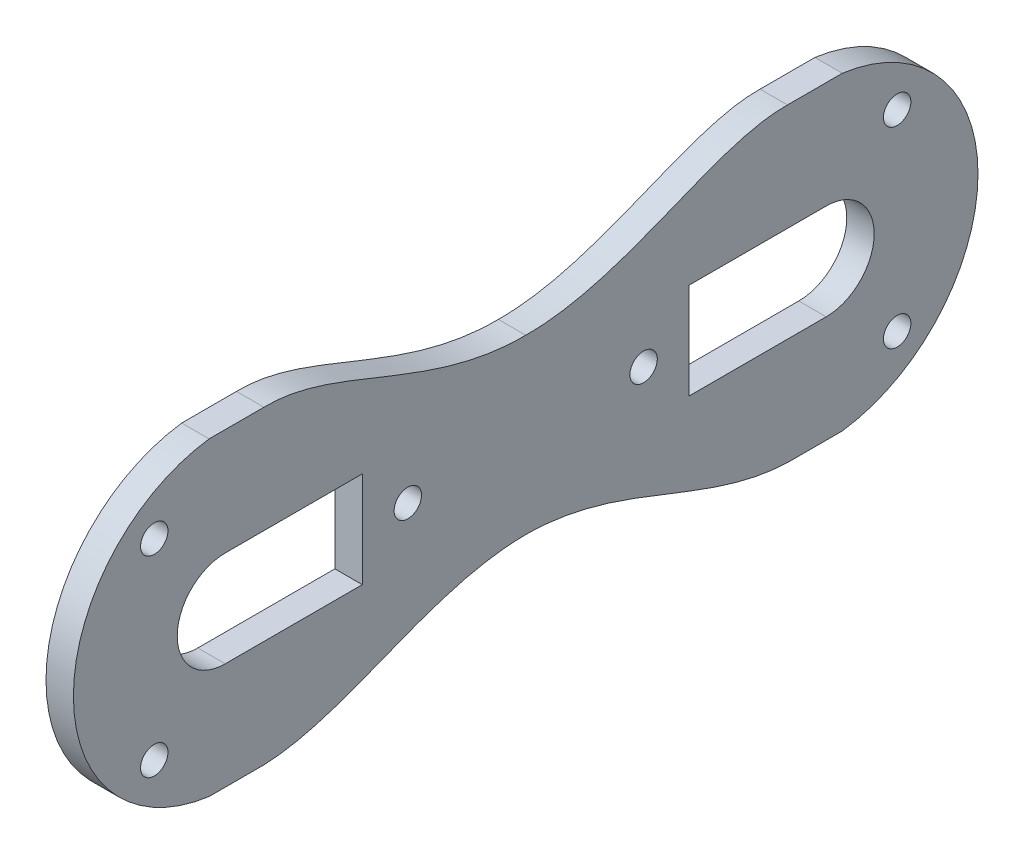
SolidWorks part; units mm, degrees
ref_plane "Piano frontale" through (0, 0, 0) normal (0, 0, 1) x (1, 0, 0)
ref_plane "Piano superiore" through (0, 0, 0) normal (0, 1, 0) x (1, 0, 0)
ref_plane "Piano destro" through (0, 0, 0) normal (1, 0, 0) x (0, 0, -1)
sketch "Schizzo1" plane through (0, 0, 0) normal (1, 0, 0) x (0, 0, -1)
  line L4 (-2.501, -10.3) -> (-2.501, -11.3)
  line L5 (-2.501, -11.3) -> (1.499, -11.3)
  line L7 (1.499, 11.3) -> (-2.501, 11.3)
  line L8 (-2.501, 11.3) -> (-2.501, 10.3)
  line L15 (-43.202, 0) -> (0, 0)
  line L16 (-43.526, 3.5) -> (-43.526, -3.5)
  line L17 (-9.676, 3.5) -> (0.324, 3.5)
  line L20 (-9.676, 3.5) -> (-9.676, -3.5)
  line L21 (-9.676, -3.5) -> (0.324, -3.5)
  line L30 (-2.501, 10.3) -> (-7.501, 10.3)
  line L31 (-7.501, 10.3) -> (-7.501, 6.3)
  line L32 (-7.501, 6.3) -> (-35.701, 6.3)
  line L35 (-21.601, 6.3) -> (-21.601, -6.3)
  line L36 (-35.701, -6.3) -> (-7.501, -6.3)
  line L37 (-7.501, -6.3) -> (-7.501, -10.3)
  line L38 (-7.501, -10.3) -> (-2.501, -10.3)
  line L39 (0.324, 3.5) -> (0.324, -3.5)
  line L40 (-35.701, -10.3) -> (-40.701, -10.3)
  line L41 (-35.701, -6.3) -> (-35.701, -10.3)
  line L42 (-35.701, 10.3) -> (-35.701, 6.3)
  line L43 (-40.701, 10.3) -> (-35.701, 10.3)
  line L44 (-33.526, -3.5) -> (-43.526, -3.5)
  line L45 (-33.526, 3.5) -> (-33.526, -3.5)
  line L46 (-33.526, 3.5) -> (-43.526, 3.5)
  line L47 (-40.701, 11.3) -> (-40.701, 10.3)
  line L48 (-44.701, 11.3) -> (-40.701, 11.3)
  line L49 (-40.701, -11.3) -> (-44.701, -11.3)
  line L50 (-40.701, -10.3) -> (-40.701, -11.3)
  arc A2 (0.324, 3.5) -> (0.324, -3.5) centre (0.324, 0) cw
  arc A11 (-44.701, 11.3) -> (-44.701, -11.3) centre (-43.202, 0) ccw
  arc A14 (1.499, 11.3) -> (1.499, -11.3) centre (0, 0) cw
  arc A15 (-43.526, 3.5) -> (-43.526, -3.5) centre (-43.526, 0) ccw
  circle A16 centre (-48.702, 7) radius 1
  circle A17 centre (-48.702, -7) radius 1
  circle A18 centre (-30.202, 0) radius 1
  circle A19 centre (-13, 0) radius 1
  circle A20 centre (5.5, 7) radius 1
  circle A21 centre (5.5, -7) radius 1
  spline S0 degree 3 poles (-2.501, 11.3) (-7.8399, 11.4296) (-14.3518, 6.2167) (-21.601, 6.3) knots 0 0 0 0 1 1 1 1
  spline S1 degree 3 poles (-2.501, -11.3) (-8.7462, -11.0636) (-14.4327, -6.3399) (-21.601, -6.3) knots 0 0 0 0 1 1 1 1
  spline S2 degree 3 poles (-40.701, -11.3) (-34.4558, -11.0636) (-28.7694, -6.3399) (-21.601, -6.3) knots 0 0 0 0 1 1 1 1
  spline S3 degree 3 poles (-40.701, 11.3) (-35.3621, 11.4296) (-28.8502, 6.2167) (-21.601, 6.3) knots 0 0 0 0 1 1 1 1
  point P7 (-9.676, 0)
  point P17 (11.399, 0)
  point P41 (-21.601, 0)
  point P53 (0, 0)
  point P54 (0, 0)
  dimension "D7" = 11.399
  dimension "D12" = 11.075
  dimension "D14" = 2
  dimension "D15" = 2
  dimension "D16" = 2
  dimension "D17" = 2
  dimension "D18" = 2
  dimension "D19" = 2
  dimension "D1" = 33
  dimension "D2" = 22.6
  dimension "D3" = 11.3
  dimension "D4" = 1
  dimension "D5" = 1
  dimension "D6" = 4
  dimension "D8" = 7
  dimension "D9" = 5
  dimension "D10" = 4
  dimension "D11" = 4
  dimension "D13" = 10
  dimension "D20" = 5.5
  dimension "D21" = 14
  dimension "D22" = 7
  dimension "D23" = 13
  dimension "D24" = 13
  dimension "D25" = 5.5
extrude "Estrusione-Estrusione1" add sketch "Schizzo1" along normal blind 2
